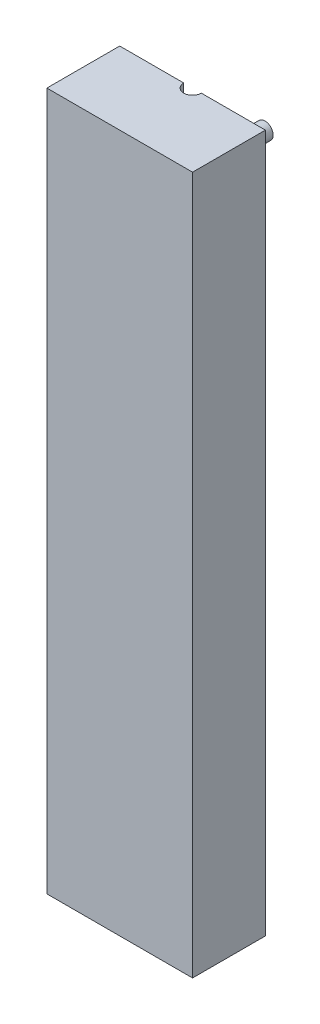
SolidWorks part; units mm, degrees
ref_plane "Front Plane" through (0, 0, 0) normal (0, 0, 1) x (1, 0, 0)
ref_plane "Top Plane" through (0, 0, 0) normal (0, 1, 0) x (1, 0, 0)
ref_plane "Right Plane" through (0, 0, 0) normal (1, 0, 0) x (0, 0, -1)
sketch "Sketch1" plane through (0, 0, 0) normal (0, 1, 0) x (1, 0, 0)
  circle A0 centre (0, 0) radius 12.5
  dimension "D1" = 25
extrude "Boss-Extrude1" add sketch "Sketch1" along normal blind 150.5
sketch "Sketch2" plane through (0, 150.5, 0) normal (0, 1, 0) x (1, 0, 0)
  line L1 (-13.5, 0) -> (13.5, 0)
  arc A0 (-13.5, 0) -> (13.5, 0) centre (0, 0) ccw
  dimension "D1" = 13.5
  dimension "D2" = 13.5
extrude "Boss-Extrude2" add sketch "Sketch2" against normal blind 148.5
sketch "Sketch8" plane through (0, 150.5, 0) normal (0, 1, 0) x (1, 0, 0)
  circle A0 centre (0, 0) radius 12.5
  dimension "D1" = 25
extrude "Cut-Extrude2" cut sketch "Sketch8" against normal through all
sketch "Sketch9" plane through (0, 150.5, 0) normal (0, 1, 0) x (1, 0, 0)
  line L0 (12.5, 0) -> (1.875, 0)
  line L1 (-1.875, 0) -> (-12.5, 0)
  arc A0 (-1.875, 0) -> (1.875, 0) centre (0, 0) ccw
  arc A1 (-12.5, 0) -> (12.5, 0) centre (0, 0) ccw
  dimension "D1" = 3.75
extrude "Boss-Extrude7" add sketch "Sketch9" against normal blind 8
sketch "Sketch11" plane through (0, 2, 0) normal (0, -1, 0) x (1, 0, 0)
  line L0 (-12.5, 0) -> (-8, 0)
  line L1 (8, 0) -> (12.5, 0)
  arc A0 (8, 0) -> (-8, 0) centre (0, 0) ccw
  arc A1 (12.5, 0) -> (-12.5, 0) centre (0, 0) ccw
  dimension "D1" = 16
extrude "Boss-Extrude8" add sketch "Sketch11" against normal blind 121
sketch "Sketch12" plane through (0, 150.5, 0) normal (0, 1, 0) x (1, 0, 0)
  line L0 (-13.5, 0) -> (-15.5, 0)
  line L1 (13.5, 0) -> (15.5, 0)
  line L3 (-15.5, 0) -> (-15.5, -15.5)
  line L4 (-15.5, -15.5) -> (15.5, -15.5)
  line L5 (15.5, -15.5) -> (15.5, 0)
  arc A2 (-13.5, 0) -> (13.5, 0) centre (0, 0) ccw
  dimension "D1" = 2
  dimension "D3" = 2
extrude "Boss-Extrude9" add sketch "Sketch12" against normal blind 148.5
sketch "Sketch13" plane through (0, 0, 0) normal (0, 0, -1) x (-1, 0, 0)
  line L0 (15.5, 2) -> (15.5, 150.5) construction
  line L1 (1.875, 150.5) -> (15.5, 150.5) construction
  circle A0 centre (12, 147) radius 1.75
  dimension "D2" = 3.5
  dimension "D3" = 3.5
  dimension "D1" = 3.5
extrude "Cut-Extrude3" cut sketch "Sketch13" against normal blind 3.5
sketch "Sketch14" plane through (0, 0, 0) normal (0, 0, -1) x (-1, 0, 0)
  line L0 (-15.5, 2) -> (-15.5, 150.5) construction
  line L1 (-15.5, 150.5) -> (-1.875, 150.5) construction
  circle A0 centre (-12, 147) radius 1.75
  dimension "D2" = 3.5
  dimension "D3" = 3.5
  dimension "D1" = 3.5
extrude "Boss-Extrude10" add sketch "Sketch14" along normal blind 3.4
sketch "Sketch15" plane through (0, 0, 0) normal (0, 0, -1) x (-1, 0, 0)
  line L0 (-15.5, 2) -> (-8, 2) construction
  line L1 (-15.5, 2) -> (-15.5, 150.5) construction
  circle A0 centre (-12, 5.5) radius 1.75
  dimension "D3" = 3.5
  dimension "D1" = 3.5
  dimension "D2" = 3.5
extrude "Cut-Extrude4" cut sketch "Sketch15" against normal blind 3.5
sketch "Sketch16" plane through (0, 0, 0) normal (0, 0, -1) x (-1, 0, 0)
  line L0 (15.5, 2) -> (15.5, 150.5) construction
  line L1 (8, 2) -> (15.5, 2) construction
  circle A0 centre (12, 5.5) radius 1.75
  dimension "D1" = 3.5
  dimension "D2" = 3.5
  dimension "D3" = 3.5
extrude "Boss-Extrude11" add sketch "Sketch16" along normal blind 3.4
